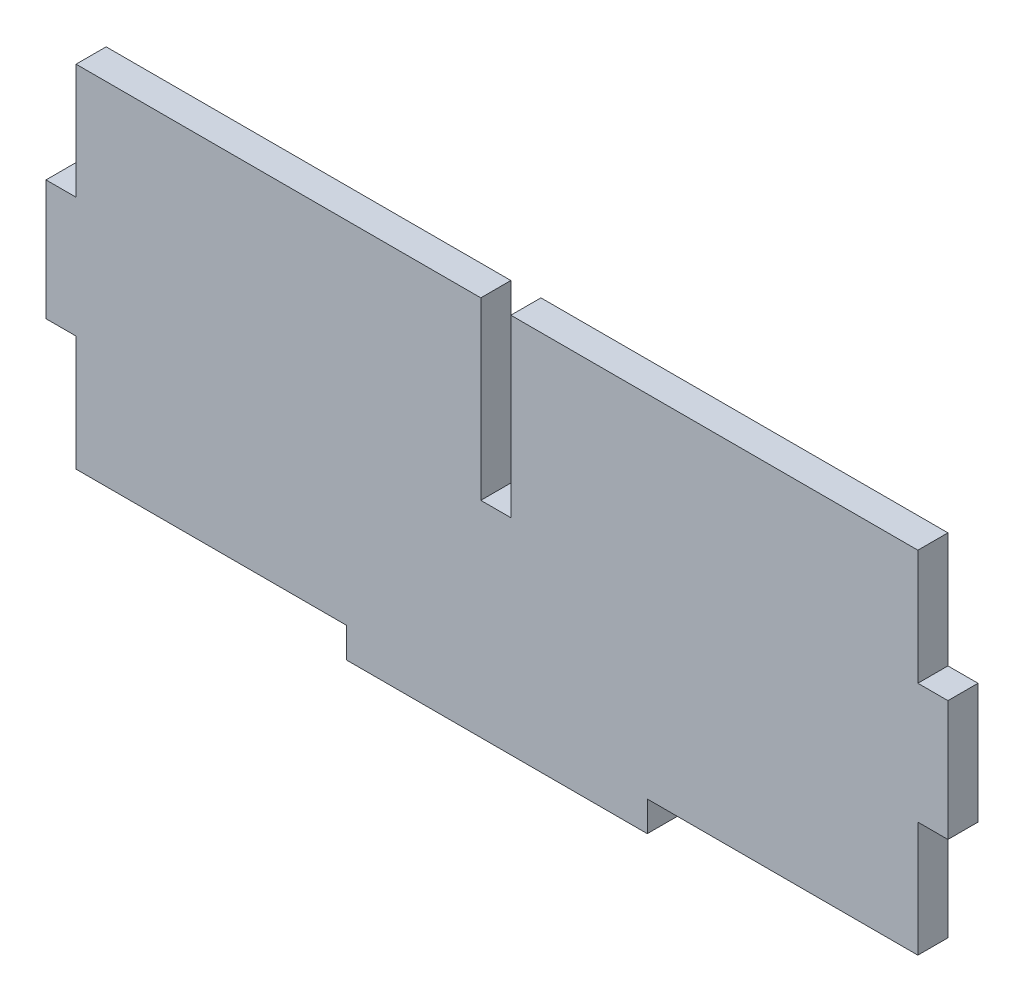
SolidWorks part; units mm, degrees
ref_plane "Front Plane" through (0, 0, 0) normal (0, 0, 1) x (1, 0, 0)
ref_plane "Top Plane" through (0, 0, 0) normal (0, 1, 0) x (1, 0, 0)
ref_plane "Right Plane" through (0, 0, 0) normal (1, 0, 0) x (0, 0, -1)
sketch "Sketch1" plane through (0, 0, 0) normal (0, 0, 1) x (1, 0, 0)
  line L0 (-42, -19) -> (-42, -4.5)
  line L1 (-45, -19) -> (45, -19)
  line L2 (-45, -19) -> (-45, 19)
  line L3 (-45, 19) -> (45, 19)
  line L4 (45, -19) -> (45, 19)
  line L5 (-45, -19) -> (45, 19) construction
  line L6 (-45, 19) -> (45, -19) construction
  line L7 (-42, -4.5) -> (-45, -4.5)
  line L8 (-45, 7.5) -> (-42, 7.5)
  line L9 (45, -4.5) -> (42, -4.5)
  line L10 (42, -4.5) -> (42, -19)
  line L11 (-42, 7.5) -> (-42, 19)
  line L12 (45, 7.5) -> (42, 7.5)
  line L13 (42, 7.5) -> (42, 19)
  line L14 (-45, -16) -> (-15, -16)
  line L15 (-15, -16) -> (-15, -19)
  line L16 (45, -16) -> (15, -16)
  line L17 (15, -16) -> (15, -19)
  line L19 (-1.613, 1.5) -> (1.387, 1.5)
  line L20 (-1.613, 1.5) -> (-1.613, 19)
  line L21 (-1.613, 19) -> (1.387, 19)
  line L22 (1.387, 1.5) -> (1.387, 19)
  line L23 (-1.613, 1.5) -> (1.387, 19) construction
  line L24 (-1.613, 19) -> (1.387, 1.5) construction
  point P0 (0, 0)
  point P23 (-0.113, 10.25)
  dimension "D1" = 90
  dimension "D2" = 38
  dimension "D3" = 11.5
  dimension "D4" = 30
  dimension "D5" = 3
  dimension "D6" = 12
  dimension "D7" = 30
  dimension "D8" = 3
  dimension "D9" = 17.5
  dimension "D10" = 3
  dimension "D11" = 12
extrude "Boss-Extrude1" add sketch "Sketch1" along normal blind 3
